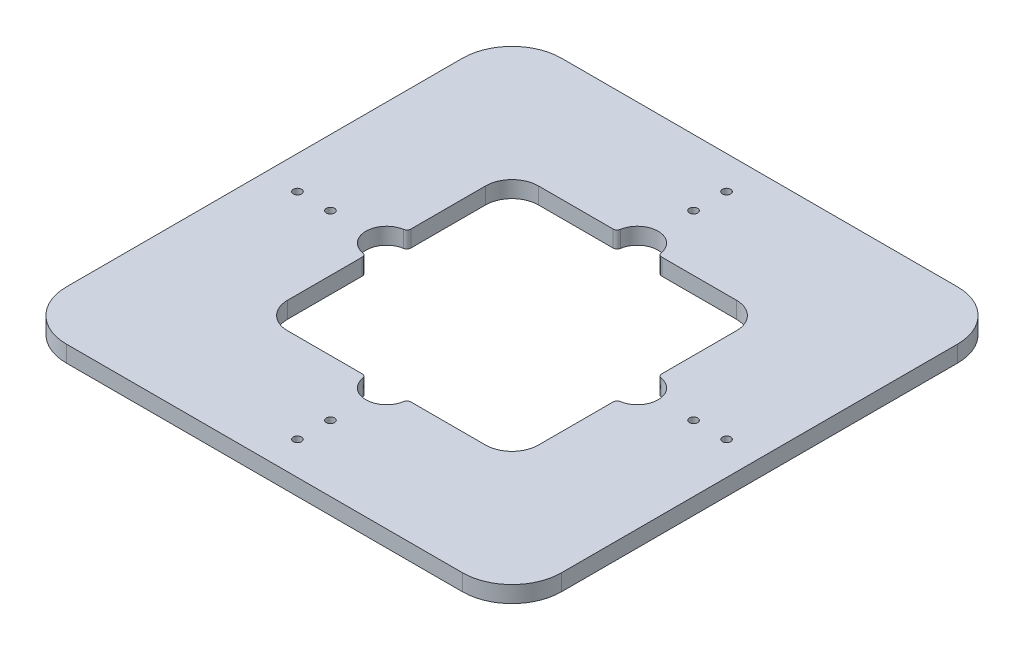
SolidWorks part; units mm, degrees
ref_plane "Front Plane" through (0, 0, 0) normal (0, 0, 1) x (1, 0, 0)
ref_plane "Top Plane" through (0, 0, 0) normal (0, 1, 0) x (1, 0, 0)
ref_plane "Right Plane" through (0, 0, 0) normal (1, 0, 0) x (0, 0, -1)
sketch "Sketch1" plane through (0, 0, 0) normal (0, 1, 0) x (1, 0, 0)
  line L0 (0, 75) -> (0, -75) construction
  line L1 (-75, -75) -> (75, -75)
  line L2 (-75, -75) -> (-75, 75)
  line L3 (-75, 75) -> (75, 75)
  line L4 (75, -75) -> (75, 75)
  line L5 (-75, -75) -> (75, 75) construction
  line L6 (-75, 75) -> (75, -75) construction
  line L7 (-75, 0) -> (75, 0) construction
  line L8 (-75, -60) -> (-60, -60) construction
  line L9 (-60, -60) -> (-60, -75) construction
  arc A2 (-75, -60) -> (-60, -75) centre (-60, -60) ccw
  arc A3 (75, -60) -> (60, -75) centre (60, -60) cw
  arc A4 (-75, 60) -> (-60, 75) centre (-60, 60) cw
  arc A5 (75, 60) -> (60, 75) centre (60, 60) ccw
  point P0 (0, 0)
  dimension "D6" = 15
  dimension "D4" = 15
  dimension "D1" = 150
  dimension "D2" = 150
extrude "Boss-Extrude3" add sketch "Sketch1" along normal blind 4 contours L4 A5 L3 A4 L2 A2 L1 A3
sketch "Sketch2" plane through (0, 4, 0) normal (0, 1, 0) x (1, 0, 0)
  line L0 (-60, 75) -> (60, 75)
  line L1 (75, 60) -> (75, -60)
  line L2 (60, -75) -> (-60, -75)
  line L3 (-75, -60) -> (-75, 60)
  line L4 (75, 0) -> (-75, 0) construction
  line L5 (0, 75) -> (0, -75) construction
  line L6 (0, 0) -> (-150, 0) construction
  line L7 (75, 0) -> (150, 0) construction
  line L8 (0, 75) -> (0, 150) construction
  line L9 (0, -75) -> (0, -150) construction
  line L10 (-150, 120) -> (-150, -120)
  line L11 (150, 120) -> (150, -120)
  line L12 (-120, 150) -> (120, 150)
  line L13 (-120, -150) -> (120, -150)
  line L14 (0, 76) -> (76, 76)
  line L15 (76, 76) -> (76, -76)
  line L16 (76, -76) -> (-76, -76)
  line L17 (-76, -76) -> (-76, 76)
  line L18 (-76, 76) -> (0, 76)
  arc A0 (-75, 60) -> (-60, 75) centre (-60, 60) cw
  arc A1 (60, 75) -> (75, 60) centre (60, 60) cw
  arc A2 (75, -60) -> (60, -75) centre (60, -60) cw
  arc A3 (-75, -60) -> (-60, -75) centre (-60, -60) ccw
  arc A4 (-120, -150) -> (-150, -120) centre (-120, -120) cw
  arc A5 (-150, 120) -> (-120, 150) centre (-120, 120) cw
  arc A6 (120, 150) -> (150, 120) centre (120, 120) cw
  arc A7 (150, -120) -> (120, -150) centre (120, -120) cw
  circle A8 centre (0, 130) radius 2.5
  circle A9 centre (0, 110) radius 2.5
  circle A10 centre (0, -110) radius 2.5
  circle A11 centre (0, -130) radius 2.5
  circle A12 centre (110, 0) radius 2.5
  circle A13 centre (130, 0) radius 2.5
  circle A14 centre (-130, 0) radius 2.5
  circle A15 centre (-110, 0) radius 2.5
  arc A16 (-60, 76) -> (-76, 60) centre (-60, 60) ccw
  arc A17 (60, 76) -> (76, 60) centre (60, 60) cw
  arc A18 (76, -60) -> (60, -76) centre (60, -60) cw
  arc A19 (-76, -60) -> (-60, -76) centre (-60, -60) ccw
  point P33 (-150, 0)
  point P36 (150, 0)
  point P39 (0, 150)
  point P42 (0, -150)
  dimension "D9" = 5
  dimension "D10" = 5
  dimension "D11" = 5
  dimension "D12" = 5
  dimension "D13" = 5
  dimension "D14" = 5
  dimension "D15" = 5
  dimension "D16" = 5
  dimension "D1" = 150
  dimension "D2" = 75
  dimension "D3" = 75
  dimension "D4" = 75
  dimension "D5" = 240
  dimension "D6" = 240
  dimension "D7" = 240
  dimension "D8" = 240
  dimension "D17" = 20
  dimension "D18" = 20
  dimension "D19" = 20
  dimension "D20" = 20
  dimension "D21" = 20
  dimension "D22" = 20
  dimension "D23" = 20
  dimension "D24" = 20
  dimension "D25" = 1
  dimension "D26" = 1
  dimension "D27" = 1
  dimension "D28" = 1
  dimension "D29" = 152
extrude "Boss-Extrude4" add sketch "Sketch2" along normal blind 10 separate body contours A19 L17 L16 | A7 L11 A6 L12 A5 L10 A4 L13 A15 A14 A13 A12 A11 A10 A9 A8 L17 L18 L14 L15 L16 | L15 A18 L16 | L14 A17 L15 | A16 L18 L17
sketch "Sketch3" plane through (0, 14, 0) normal (0, 1, 0) x (1, 0, 0)
  line L0 (-60, 76) -> (60, 76)
  line L1 (76, 60) -> (76, -60)
  line L2 (60, -76) -> (-60, -76)
  line L3 (-76, -60) -> (-76, 60)
  arc A0 (60, 76) -> (76, 60) centre (60, 60) cw
  arc A1 (76, -60) -> (60, -76) centre (60, -60) cw
  arc A2 (-60, -76) -> (-76, -60) centre (-60, -60) cw
  arc A3 (-76, 60) -> (-60, 76) centre (-60, 60) cw
extrude "Cut-Extrude1" cut sketch "Sketch3" against normal blind 52
sketch "Sketch4" plane through (0, 14, 0) normal (0, 1, 0) x (1, 0, 0)
  line L0 (-60, 76) -> (60, 76) construction
  line L1 (60, -76) -> (-60, -76) construction
  line L2 (-76, -60) -> (-76, 60) construction
  line L3 (76, 60) -> (76, -60) construction
  circle A0 centre (0, 76) radius 12.5
  circle A1 centre (0, -76) radius 12.5
  circle A2 centre (-76, 0) radius 12.5
  circle A3 centre (76, 0) radius 12.5
  circle A4 centre (-14.7902, 78.5) radius 2.5
  circle A5 centre (14.7902, 78.5) radius 2.5
  circle A6 centre (78.5, -14.7902) radius 2.5
  circle A7 centre (78.5, 14.7902) radius 2.5
  circle A8 centre (-14.7902, -78.5) radius 2.5
  circle A9 centre (14.7902, -78.5) radius 2.5
  circle A10 centre (-78.5, 14.7902) radius 2.5
  circle A11 centre (-78.5, -14.7902) radius 2.5
  point P35 (0, 0)
  line M6 (-76, -60) -> (-76, 60)
  line M8 (-60, 76) -> (60, 76)
  line M10 (76, 60) -> (76, -60)
  line M12 (60, -76) -> (-60, -76)
  dimension "D1" = 25
  dimension "D2" = 25
  dimension "D3" = 25
  dimension "D4" = 25
  dimension "D5" = 5
  dimension "D6" = 5
  dimension "D7" = 4
extrude "Cut-Extrude2" cut sketch "Sketch4" against normal blind 10 contours A0 M8 | A0 M8 | A4 A0 M8 | A5 A0 M8 | A2 M6 | A2 M6 | A10 A2 M6 | A11 A2 M6 | A1 M12 | A1 M12 | A8 A1 M12 | A9 A1 M12 | A3 M10 | A3 M10 | A7 A3 M10 | A6 A3 M10
